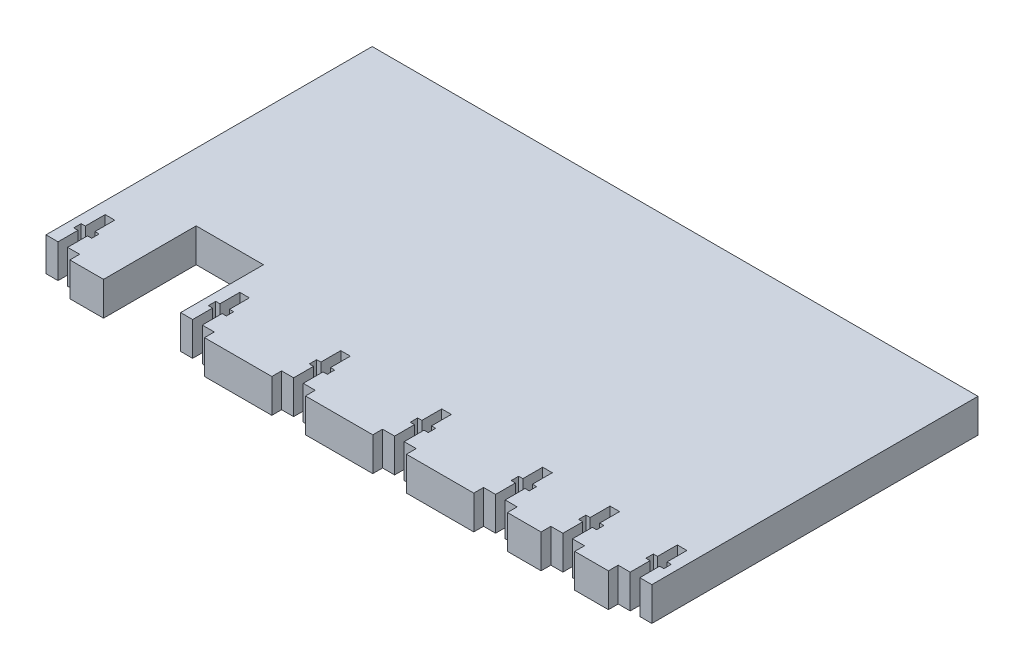
SolidWorks part; units mm, degrees
ref_plane "Front Plane" through (0, 0, 0) normal (0, 0, 1) x (1, 0, 0)
ref_plane "Top Plane" through (0, 0, 0) normal (0, 1, 0) x (1, 0, 0)
ref_plane "Right Plane" through (0, 0, 0) normal (1, 0, 0) x (0, 0, -1)
sketch "Sketch1" plane through (0, 0, 0) normal (0, 1, 0) x (1, 0, 0)
  line L0 (90, -48.4544) -> (80, -48.4544)
  line L1 (90, -48.4544) -> (-90, -48.4544)
  line L2 (90, -48.4544) -> (90, 48.4544)
  line L3 (90, 48.4544) -> (-90, 48.4544)
  line L4 (-90, -48.4544) -> (-90, 48.4544)
  line L5 (90, -48.4544) -> (-90, 48.4544) construction
  line L6 (90, 48.4544) -> (-90, -48.4544) construction
  line L7 (80, -48.4544) -> (80, -51.3617)
  line L8 (80, -51.3617) -> (70, -51.3617)
  line L9 (70, -51.3617) -> (70, -48.4544)
  line L10 (70, -48.4544) -> (60, -48.4544)
  line L11 (60, -48.4544) -> (60, -51.3617)
  line L12 (60, -51.3617) -> (50, -51.3617)
  line L13 (50, -51.3617) -> (50, -48.4544)
  line L14 (50, -48.4544) -> (40, -48.4544)
  line L15 (40, -48.4544) -> (40, -51.3617)
  line L16 (40, -51.3617) -> (20, -51.3617)
  line L17 (20, -51.3617) -> (20, -48.4544)
  line L18 (20, -48.4544) -> (10, -48.4544)
  line L19 (10, -48.4544) -> (10, -51.3617)
  line L20 (10, -51.3617) -> (-10, -51.3617)
  line L21 (-10, -51.3617) -> (-10, -48.4544)
  line L22 (-10, -48.4544) -> (-20, -48.4544)
  line L23 (-20, -48.4544) -> (-20, -51.3617)
  line L24 (-20, -51.3617) -> (-40, -51.3617)
  line L25 (-40, -51.3617) -> (-40, -48.4544)
  line L26 (-40, -48.4544) -> (-50, -48.4544)
  line L27 (-50, -48.4544) -> (-50, -23.8396)
  line L28 (-50, -23.8396) -> (-70, -23.8396)
  line L29 (-70, -23.8396) -> (-70, -48.4544)
  line L30 (-70, -48.4544) -> (-70, -51.3617)
  line L31 (-70, -51.3617) -> (-80, -51.3617)
  line L32 (-80, -51.3617) -> (-80, -48.4544)
  line L33 (-80, -48.4544) -> (-90, -48.4544)
  point P0 (0, 0)
  dimension "D1" = 10
  dimension "D2" = 10
  dimension "D3" = 10
  dimension "D4" = 10
  dimension "D5" = 10
  dimension "D6" = 20
  dimension "D7" = 10
  dimension "D8" = 20
  dimension "D9" = 10
  dimension "D10" = 20
  dimension "D11" = 10
  dimension "D12" = 20
  dimension "D13" = 10
  dimension "D14" = 10
extrude "Boss-Extrude1" add sketch "Sketch1" along normal blind 10 contours L29 L28 L27 L1 L0 L2 L3 L4 | L32 L31 L30 L1 | L25 L24 L23 L1 | L21 L20 L19 L1 | L17 L16 L15 L1 | L13 L12 L11 L1 | L9 L8 L7 L1
sketch "Sketch3" plane through (0, 10, 0) normal (0, 1, 0) x (1, 0, 0)
  line L0 (-80, -48.4544) -> (-90, -48.4544) construction
  line L1 (-86.425, -48.4544) -> (-83.575, -48.4544)
  line L2 (-86.425, -48.4544) -> (-86.425, -34.4544)
  line L3 (-86.425, -34.4544) -> (-83.575, -34.4544)
  line L4 (-83.575, -48.4544) -> (-83.575, -34.4544)
  line L5 (-90, -48.4544) -> (-90, 48.4544) construction
  line L6 (-87.675, -40.3544) -> (-82.325, -40.3544)
  line L7 (-87.675, -40.3544) -> (-87.675, -42.5544)
  line L8 (-87.675, -42.5544) -> (-82.325, -42.5544)
  line L9 (-82.325, -40.3544) -> (-82.325, -42.5544)
  line L10 (-46.425, -48.4544) -> (-43.575, -48.4544)
  line L11 (-46.425, -48.4544) -> (-46.425, -34.4544)
  line L12 (-46.425, -34.4544) -> (-43.575, -34.4544)
  line L13 (-43.575, -48.4544) -> (-43.575, -34.4544)
  line L14 (-47.675, -40.3544) -> (-42.325, -40.3544)
  line L15 (-47.675, -40.3544) -> (-47.675, -42.5544)
  line L16 (-47.675, -42.5544) -> (-42.325, -42.5544)
  line L17 (-42.325, -40.3544) -> (-42.325, -42.5544)
  line L18 (-40, -48.4544) -> (-50, -48.4544) construction
  line L19 (-50, -48.4544) -> (-50, -23.8396) construction
  line L20 (-16.425, -48.4544) -> (-13.575, -48.4544)
  line L21 (-16.425, -48.4544) -> (-16.425, -34.4544)
  line L22 (-16.425, -34.4544) -> (-13.575, -34.4544)
  line L23 (-13.575, -48.4544) -> (-13.575, -34.4544)
  line L24 (-17.675, -40.3544) -> (-12.325, -40.3544)
  line L25 (-17.675, -40.3544) -> (-17.675, -42.5544)
  line L26 (-17.675, -42.5544) -> (-12.325, -42.5544)
  line L27 (-12.325, -40.3544) -> (-12.325, -42.5544)
  line L28 (13.575, -48.4544) -> (16.425, -48.4544)
  line L29 (13.575, -48.4544) -> (13.575, -34.4544)
  line L30 (13.575, -34.4544) -> (16.425, -34.4544)
  line L31 (16.425, -48.4544) -> (16.425, -34.4544)
  line L32 (12.325, -40.3544) -> (17.675, -40.3544)
  line L33 (12.325, -40.3544) -> (12.325, -42.5544)
  line L34 (12.325, -42.5544) -> (17.675, -42.5544)
  line L35 (17.675, -40.3544) -> (17.675, -42.5544)
  line L36 (43.575, -48.4544) -> (46.425, -48.4544)
  line L37 (43.575, -48.4544) -> (43.575, -34.4544)
  line L38 (43.575, -34.4544) -> (46.425, -34.4544)
  line L39 (46.425, -48.4544) -> (46.425, -34.4544)
  line L40 (42.325, -40.3544) -> (47.675, -40.3544)
  line L41 (42.325, -40.3544) -> (42.325, -42.5544)
  line L42 (42.325, -42.5544) -> (47.675, -42.5544)
  line L43 (47.675, -40.3544) -> (47.675, -42.5544)
  line L44 (63.575, -48.4544) -> (66.425, -48.4544)
  line L45 (63.575, -48.4544) -> (63.575, -34.4544)
  line L46 (63.575, -34.4544) -> (66.425, -34.4544)
  line L47 (66.425, -48.4544) -> (66.425, -34.4544)
  line L48 (62.325, -40.3544) -> (67.675, -40.3544)
  line L49 (62.325, -40.3544) -> (62.325, -42.5544)
  line L50 (62.325, -42.5544) -> (67.675, -42.5544)
  line L51 (67.675, -40.3544) -> (67.675, -42.5544)
  line L52 (83.575, -48.4544) -> (86.425, -48.4544)
  line L53 (83.575, -48.4544) -> (83.575, -34.4544)
  line L54 (83.575, -34.4544) -> (86.425, -34.4544)
  line L55 (86.425, -48.4544) -> (86.425, -34.4544)
  line L56 (82.325, -40.3544) -> (87.675, -40.3544)
  line L57 (82.325, -40.3544) -> (82.325, -42.5544)
  line L58 (82.325, -42.5544) -> (87.675, -42.5544)
  line L59 (87.675, -40.3544) -> (87.675, -42.5544)
  line L60 (90, -48.4544) -> (80, -48.4544) construction
  line L61 (90, -48.4544) -> (90, 48.4544) construction
  line L62 (70, -48.4544) -> (60, -48.4544) construction
  line L63 (70, -51.3617) -> (70, -48.4544) construction
  line L64 (50, -48.4544) -> (40, -48.4544) construction
  line L65 (50, -51.3617) -> (50, -48.4544) construction
  line L66 (20, -48.4544) -> (10, -48.4544) construction
  line L67 (20, -51.3617) -> (20, -48.4544) construction
  line L68 (-10, -48.4544) -> (-20, -48.4544) construction
  line L69 (-10, -51.3617) -> (-10, -48.4544) construction
  point P20 (-47.675, -41.4544)
  point P33 (-17.675, -41.4544)
  point P42 (12.325, -41.4544)
  point P51 (42.325, -41.4544)
  point P60 (62.325, -41.4544)
  point P69 (82.325, -41.4544)
  dimension "D1" = 2.85
  dimension "D2" = 5.35
  dimension "D3" = 2.2
  dimension "D4" = 14
  dimension "D5" = 2.325
  dimension "D6" = 3.575
  dimension "D7" = 2.85
  dimension "D8" = 5.35
  dimension "D9" = 2.2
  dimension "D10" = 14
  dimension "D11" = 1.25
  dimension "D12" = 5.9
  dimension "D13" = 5.9
  dimension "D14" = 0
  dimension "D15" = 3.575
  dimension "D16" = 2.85
  dimension "D17" = 5.35
  dimension "D18" = 2.2
  dimension "D19" = 14
  dimension "D20" = 1.25
  dimension "D21" = 5.9
  dimension "D22" = 2.85
  dimension "D23" = 5.35
  dimension "D24" = 2.2
  dimension "D25" = 14
  dimension "D26" = 1.25
  dimension "D27" = 5.9
  dimension "D28" = 2.85
  dimension "D29" = 5.35
  dimension "D30" = 2.2
  dimension "D31" = 14
  dimension "D32" = 1.25
  dimension "D33" = 5.9
  dimension "D34" = 2.85
  dimension "D35" = 5.35
  dimension "D36" = 2.2
  dimension "D37" = 14
  dimension "D38" = 1.25
  dimension "D39" = 5.9
  dimension "D40" = 2.85
  dimension "D41" = 5.35
  dimension "D42" = 2.2
  dimension "D43" = 14
  dimension "D44" = 1.25
  dimension "D45" = 5.9
  dimension "D46" = 0
  dimension "D47" = 3.575
  dimension "D48" = 0
  dimension "D49" = 3.575
  dimension "D50" = 0
  dimension "D51" = 3.575
  dimension "D52" = 0
  dimension "D53" = 3.575
  dimension "D54" = 0
  dimension "D55" = 3.575
extrude "Cut-Extrude1" cut sketch "Sketch3" against normal blind 10 contours L4 L3 L2 L1 | L9 L8 L7 L6 | L13 L12 L11 L10 | L17 L16 L15 L14 | L23 L22 L21 L20 | L27 L26 L25 L24 | L29 L30 L31 L28 | L33 L34 L35 L32 | L39 L38 L37 L36 | L42 L43 L40 L41 | L50 L51 L48 L49 | L45 L46 L47 L44 | L55 L54 L53 L52 | L58 L59 L56 L57
